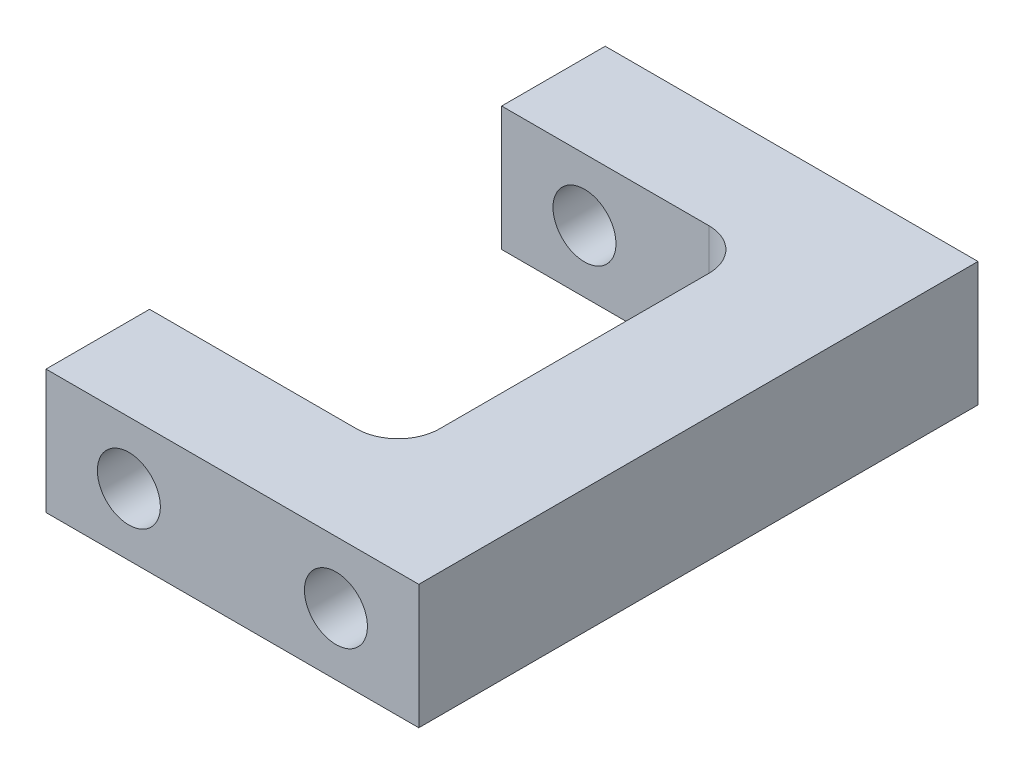
SolidWorks part; units mm, degrees
ref_plane "Front Plane" through (0, 0, 0) normal (0, 0, 1) x (1, 0, 0)
ref_plane "Top Plane" through (0, 0, 0) normal (0, 1, 0) x (1, 0, 0)
ref_plane "Right Plane" through (0, 0, 0) normal (1, 0, 0) x (0, 0, -1)
sketch "Sketch1" plane through (0, 0, 0) normal (0, 0, 1) x (1, 0, 0)
  line L0 (-25, 0) -> (0, 0) construction
  line L1 (0, 0) -> (25, 0) construction
  line L2 (-45, -15) -> (-45, 15)
  line L3 (-45, 15) -> (45, 15)
  line L4 (45, 15) -> (45, -15)
  line L5 (45, -15) -> (-45, -15)
  point P11 (0, -15)
  point P12 (45, 0)
  dimension "D3" = 25
  dimension "D4" = 25
  dimension "D5" = 90
  dimension "D8" = 30
extrude "Boss-Extrude1" add sketch "Sketch1" along normal blind 25
sketch "Sketch2" plane through (45, 0, 0) normal (1, 0, 0) x (0, 0, -1)
  line L0 (-25, 15) -> (0, 15) construction
  line L1 (0, -15) -> (-110, -15)
  line L2 (0, -15) -> (0, 15)
  line L3 (0, 15) -> (-110, 15)
  line L4 (-110, -15) -> (-110, 15)
  dimension "D1" = 110
extrude "Boss-Extrude2" add sketch "Sketch2" against normal blind 30
sketch "Sketch3" plane through (45, 0, 0) normal (1, 0, 0) x (0, 0, -1)
  line L0 (0, 15) -> (-110, 15) construction
  line L1 (-110, -15) -> (-135, -15)
  line L2 (-110, -15) -> (-110, 15)
  line L3 (-110, 15) -> (-135, 15)
  line L4 (-135, -15) -> (-135, 15)
  dimension "D1" = 25
extrude "Boss-Extrude3" add sketch "Sketch3" along normal up to surface (90 mm away)
sketch "Sketch4" plane through (0, 0, 0) normal (0, 0, -1) x (-1, 0, 0)
  line L0 (45, 0) -> (25, 0) construction
  line L1 (45, 15) -> (45, -15) construction
  line L2 (25, 0) -> (-25, 0) construction
  line L3 (-25, 0) -> (-45, 0) construction
  line L4 (-45, -15) -> (-45, 15) construction
  circle A0 centre (25, 0) radius 7.6
  circle A1 centre (-25, 0) radius 7.6
  dimension "D2" = 15.2
  dimension "D3" = 15.2
  dimension "D1" = 50
extrude "Cut-Extrude1" cut sketch "Sketch4" against normal through all
fillet "Fillet1" radius 10 2 edges at (15, 0, 110) (15, 0, 25)
